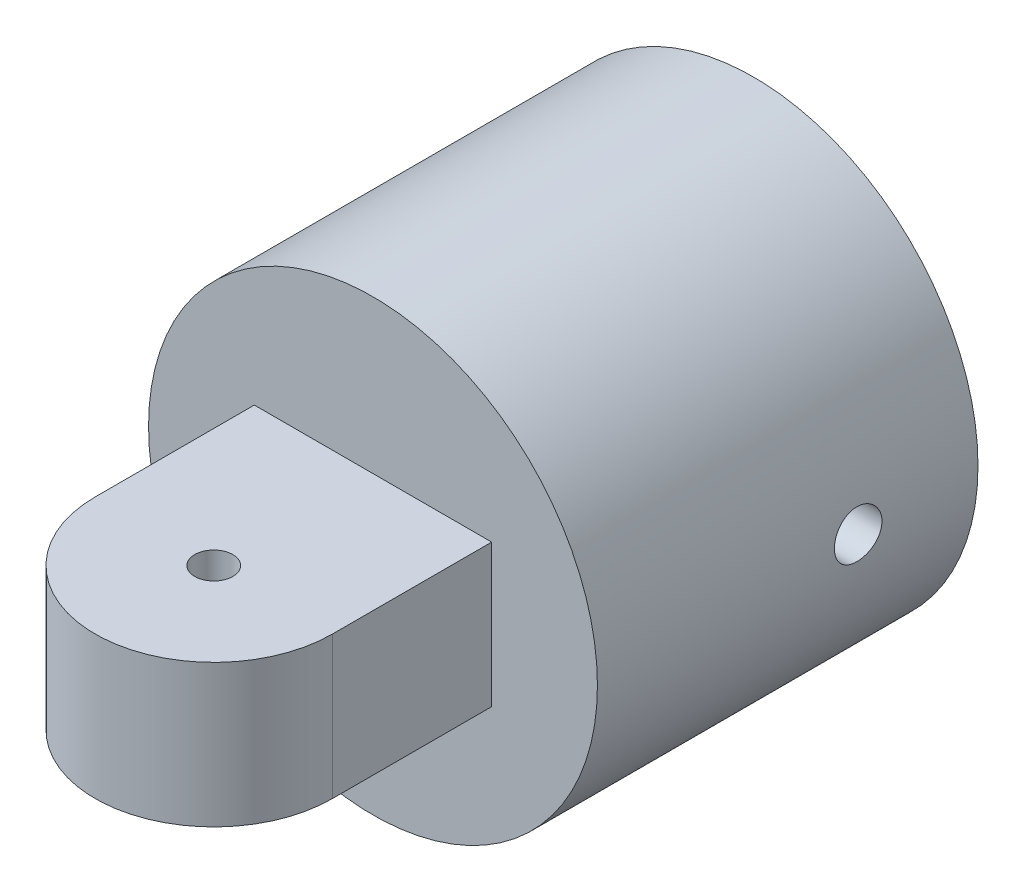
SolidWorks part; units mm, degrees
ref_plane "Plano frontal" through (0, 0, 0) normal (0, 0, 1) x (1, 0, 0)
ref_plane "Plano superior" through (0, 0, 0) normal (0, 1, 0) x (1, 0, 0)
ref_plane "Plano direito" through (0, 0, 0) normal (1, 0, 0) x (0, 0, -1)
sketch "Esboço1" plane through (0, 0, 0) normal (0, 0, 1) x (1, 0, 0)
  circle A0 centre (0, 0) radius 23.59
extrude "Ressalto-extrusão1" add sketch "Esboço1" along normal blind 30 and the other way blind 10
sketch "Esboço2" plane through (0, 0, 0) normal (0, 1, 0) x (1, 0, 0)
  line L0 (-12.4735, -30) -> (12.4735, -30)
  line L1 (-23.59, -30) -> (23.59, -30) construction
  line L2 (-12.4735, -30) -> (-12.4735, -46.7347)
  line L4 (12.4735, -46.7347) -> (12.4735, -30)
  arc A0 (-12.4735, -46.7347) -> (12.4735, -46.7347) centre (0, -46.7347) ccw
  point P5 (0, -30)
extrude "Ressalto-extrusão2" add sketch "Esboço2" along normal mid plane 14.98 separate body
sketch "Esboço3" plane through (0, 7.49, 0) normal (0, 1, 0) x (1, 0, 0)
  circle A0 centre (0, -46.7347) radius 2
extrude "Corte-extrusão1" cut sketch "Esboço3" against normal mid plane 75
ref_plane "Plano1" through (-22.4735, 0, 0) normal (-1, 0, 0) x (0, 0, 1)
sketch "Esboço4" plane through (-22.4735, 0, 0) normal (-1, 0, 0) x (0, 0, 1)
  circle A0 centre (2.5927, 0) radius 2.5
extrude "Corte-extrusão2" cut sketch "Esboço4" against normal mid plane 160
